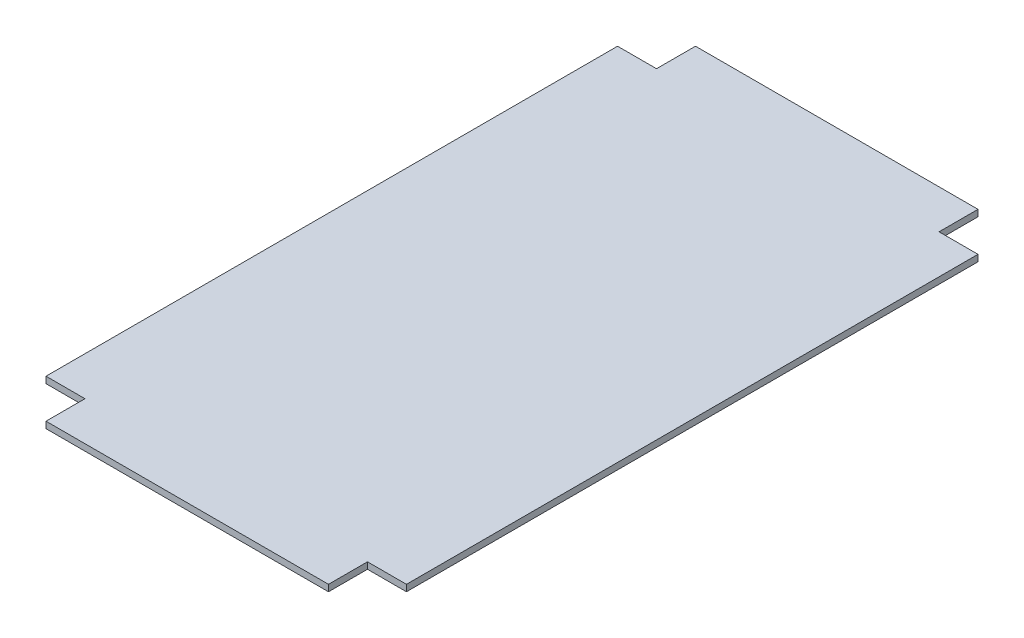
SolidWorks part; units mm, degrees
material "Plain Carbon Steel"
ref_plane "Front Plane" through (0, 0, 0) normal (0, 0, 1) x (1, 0, 0)
ref_plane "Top Plane" through (0, 0, 0) normal (0, 1, 0) x (1, 0, 0)
ref_plane "Right Plane" through (0, 0, 0) normal (1, 0, 0) x (0, 0, -1)
sketch "Sketch1" plane through (0, 0, 0) normal (0, 1, 0) x (1, 0, 0)
  line L1 (138.74, -220) -> (-138.74, -220)
  line L2 (138.74, -220) -> (138.74, 220)
  line L3 (138.74, 220) -> (-138.74, 220)
  line L4 (-138.74, -220) -> (-138.74, 220)
  line L5 (138.74, -220) -> (-138.74, 220) construction
  line L6 (138.74, 220) -> (-138.74, -220) construction
  point P0 (0, 0)
  dimension "D1" = 277.48
  dimension "D2" = 440
extrude "Boss-Extrude1" add sketch "Sketch1" along normal blind 5
sketch "Sketch2" plane through (0, 5, 0) normal (0, 1, 0) x (1, 0, 0)
  line L0 (-138.74, 220) -> (-108.74, 220) construction
  line L1 (138.74, 220) -> (-138.74, 220) construction
  line L2 (138.74, 220) -> (108.74, 220) construction
  line L7 (0, 0) -> (39.2522, 0) construction
  line L8 (-108.74, 220) -> (108.74, 220)
  line L9 (-108.74, 220) -> (-108.74, 250)
  line L10 (-108.74, 250) -> (108.74, 250)
  line L11 (108.74, 220) -> (108.74, 250)
  line L12 (-108.74, 220) -> (108.74, 250) construction
  line L13 (-108.74, 250) -> (108.74, 220) construction
  line L14 (108.74, -220) -> (108.74, -250)
  line L15 (-108.74, -220) -> (108.74, -220)
  line L16 (-108.74, -220) -> (-108.74, -250)
  line L17 (-108.74, -250) -> (108.74, -250)
  point P7 (0, 235)
  point P8 (-2.992, 235)
extrude "Boss-Extrude2" add sketch "Sketch2" against normal blind 5
